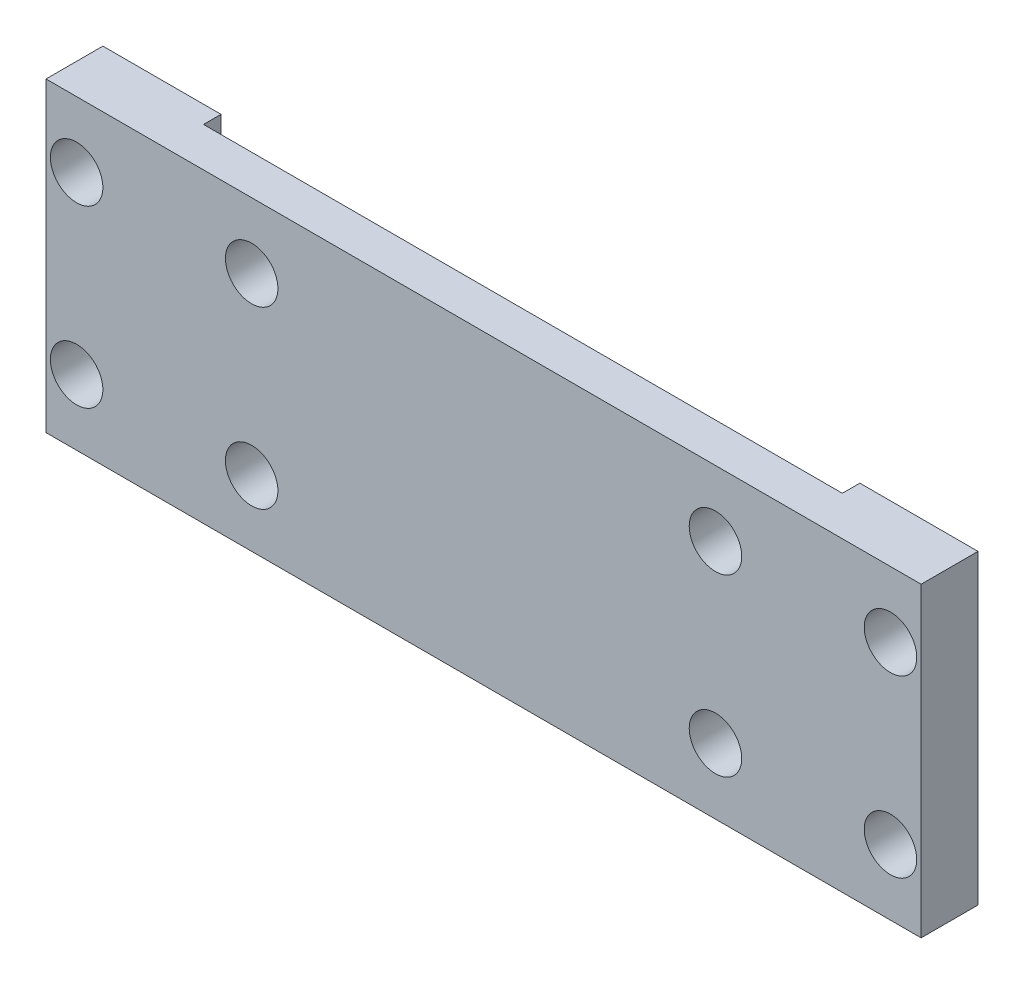
SolidWorks part; units mm, degrees
ref_plane "Plan de face" through (0, 0, 0) normal (0, 0, 1) x (1, 0, 0)
ref_plane "Plan de dessus" through (0, 0, 0) normal (0, 1, 0) x (1, 0, 0)
ref_plane "Plan de droite" through (0, 0, 0) normal (1, 0, 0) x (0, 0, -1)
sketch "Esquisse1" plane through (0, 0, 0) normal (0, 0, 1) x (1, 0, 0)
  line L0 (-36.5, 0) -> (36.5, 0) construction
  line L1 (-36.5, 0) -> (-50, 0)
  line L2 (-36.5, 0) -> (-36.5, -35)
  line L3 (-36.5, -35) -> (-50, -35)
  line L4 (-50, 0) -> (-50, -35)
  line L9 (-50, -17.5) -> (-36.5, -17.5) construction
  line L10 (-46.5, -7.5) -> (-46.5, -27.5) construction
  line L11 (0, 0) -> (0, -35) construction
  line L12 (36.5, -35) -> (50, -35)
  line L13 (50, 0) -> (50, -35)
  line L14 (36.5, 0) -> (50, 0)
  line L15 (36.5, 0) -> (36.5, -35)
  circle A0 centre (-46.5, -7.5) radius 1.75
  circle A1 centre (-46.5, -27.5) radius 1.75
  circle A2 centre (46.5, -27.5) radius 1.75
  circle A3 centre (46.5, -7.5) radius 1.75
  point P8 (0, 0)
  point P15 (-46.5, -17.5)
  dimension "D3" = 3.5
  dimension "D1" = 73
  dimension "D2" = 13.5
  dimension "D4" = 20
  dimension "D5" = 35
  dimension "D6" = 3.5
extrude "Boss.-Extru.1" add sketch "Esquisse1" along normal blind 2
sketch "Esquisse2" plane through (0, 0, 2) normal (0, 0, 1) x (1, 0, 0)
  line L0 (0, 0) -> (0, -35) construction
  line L1 (-50, 0) -> (50, 0)
  line L2 (-50, 0) -> (-50, -35)
  line L3 (-50, -35) -> (50, -35)
  line L4 (50, 0) -> (50, -35)
  line L5 (-26.5, -7.5) -> (-26.5, -27.5) construction
  line L6 (-26.5, -7.5) -> (-46.5, -7.5) construction
  circle A0 centre (-46.5, -7.5) radius 3
  circle A1 centre (-46.5, -27.5) radius 3
  circle A2 centre (46.5, -7.5) radius 3
  circle A3 centre (46.5, -27.5) radius 3
  circle A4 centre (-26.5, -7.5) radius 3
  circle A5 centre (-26.5, -27.5) radius 3
  circle A6 centre (26.5, -27.5) radius 3
  circle A7 centre (26.5, -7.5) radius 3
  dimension "D1" = 6
  dimension "D2" = 20
  dimension "D3" = 20
extrude "Boss.-Extru.2" add sketch "Esquisse2" along normal blind 4.5
